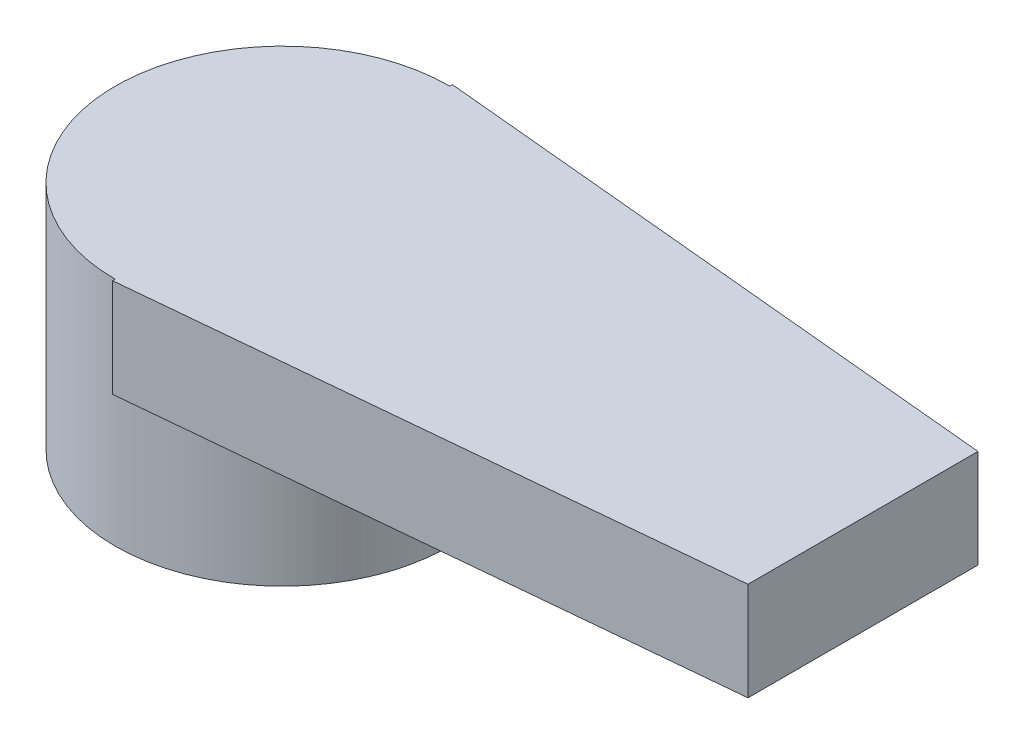
SolidWorks part; units mm, degrees
material "ABS"
ref_plane "Front Plane" through (0, 0, 0) normal (0, 0, 1) x (1, 0, 0)
ref_plane "Top Plane" through (0, 0, 0) normal (0, 1, 0) x (1, 0, 0)
ref_plane "Right Plane" through (0, 0, 0) normal (1, 0, 0) x (0, 0, -1)
sketch "Sketch1" plane through (0, 0, 0) normal (0, 1, 0) x (1, 0, 0)
  circle A0 centre (0, 0) radius 3.4
extrude "Boss-Extrude1" add sketch "Sketch1" along normal mid plane 4.7 from offset 19.3
sketch "Sketch2" plane through (0, 0, 0) normal (0, 1, 0) x (1, 0, 0)
  line L0 (0, 3.4531) -> (11.8, 2.3377)
  line L1 (11.8, 2.3377) -> (11.8, -2.3377)
  line L2 (11.8, -2.3377) -> (0, -3.4531)
  line L3 (0, -3.4531) -> (0, 3.4531)
extrude "Boss-Extrude2" add sketch "Sketch2" along normal mid plane 2 from offset 20.65
sketch "Sketch3" plane through (0, 0, 0) normal (0, 1, 0) x (1, 0, 0)
  circle A0 centre (0, 0) radius 2.45
extrude "Cut-Extrude1" cut sketch "Sketch3" against normal mid plane 2.7 from offset 18.3
